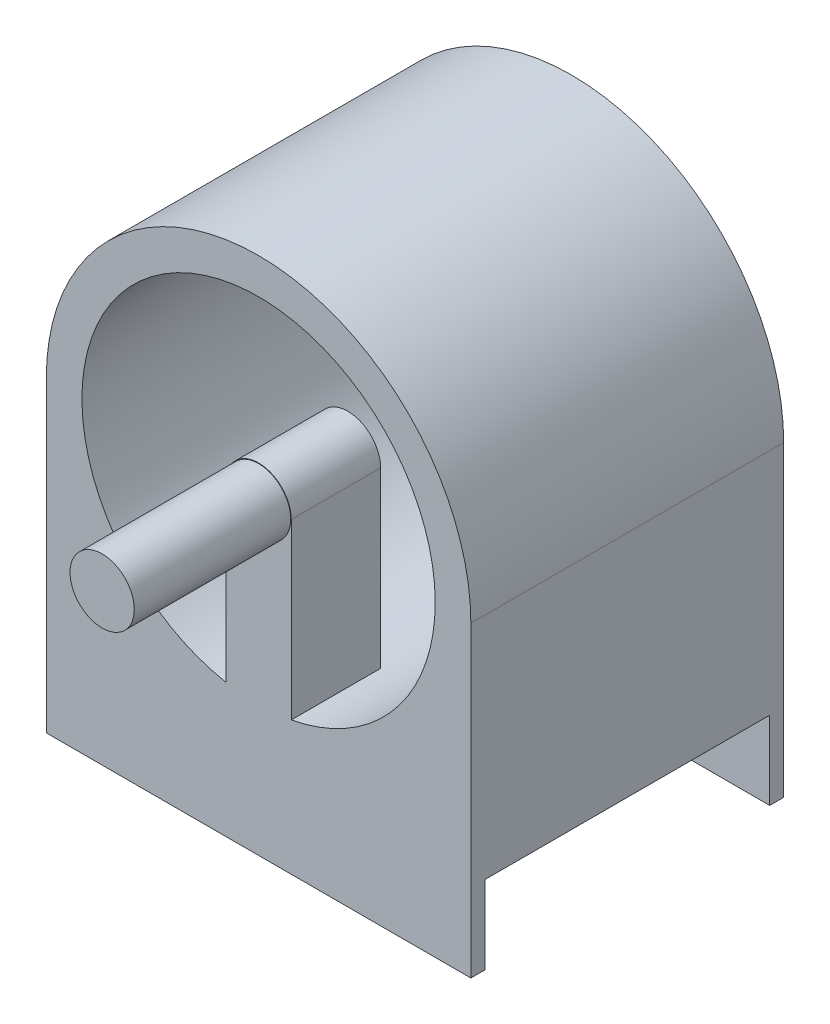
SolidWorks part; units mm, degrees
ref_plane "Front Plane" through (0, 0, 0) normal (0, 0, 1) x (1, 0, 0)
ref_plane "Top Plane" through (0, 0, 0) normal (0, 1, 0) x (1, 0, 0)
ref_plane "Right Plane" through (0, 0, 0) normal (1, 0, 0) x (0, 0, -1)
sketch "Sketch1" plane through (0, 0, 0) normal (1, 0, 0) x (0, 0, -1)
  line L0 (-12.75, 0) -> (-12.75, 7)
  line L1 (-12.75, 7) -> (12.75, 7)
  line L2 (12.75, 7) -> (12.75, 0)
  line L3 (12.75, 0) -> (14, 0)
  line L4 (14, 0) -> (14, 8.5)
  line L5 (14, 8.5) -> (-14, 8.5)
  line L6 (-14, 8.5) -> (-14, 0)
  line L7 (-14, 0) -> (-12.75, 0)
  point P2 (0, 7)
  dimension "D1" = 1.25
  dimension "D2" = 1.25
  dimension "D3" = 1.5
  dimension "D4" = 7
  dimension "D5" = 7
  dimension "D6" = 25.5
extrude "Boss-Extrude1" add sketch "Sketch1" along normal blind 38
sketch "Sketch2" plane through (0, 0, 0) normal (0, 0, 1) x (1, 0, 0)
  line L0 (38, 8.5) -> (0, 8.5) construction
  line L1 (0, 27.5) -> (0, 8.5)
  line L2 (38, 27.5) -> (38, 8.5)
  line L3 (38, 8.5) -> (0, 8.5)
  arc A0 (38, 27.5) -> (0, 27.5) centre (19, 27.5) ccw
  point P7 (19, 8.5)
  dimension "D1" = 38
extrude "Boss-Extrude2" add sketch "Sketch2" along normal mid plane 28
sketch "Sketch3" plane through (0, 0, 14) normal (0, 0, 1) x (1, 0, 0)
  circle A0 centre (19, 27.5) radius 15.81
  dimension "D1" = 31.62
extrude "Cut-Extrude1" cut sketch "Sketch3" against normal through all
sketch "Sketch4" plane through (0, 0, 14) normal (0, 0, 1) x (1, 0, 0)
  line L0 (21.925, 27.5) -> (21.925, 11.9629)
  line L1 (16.075, 27.5) -> (16.075, 11.9629)
  arc A0 (21.925, 27.5) -> (16.075, 27.5) centre (19, 27.5) ccw
  circle A2 centre (19, 27.5) radius 15.81 construction
  arc A3 (16.075, 11.9629) -> (21.925, 11.9629) centre (19, 27.5) ccw
  dimension "D1" = 5.85
extrude "Boss-Extrude3" add sketch "Sketch4" against normal blind 8 contours A0 L1 A3 L0
sketch "Sketch5" plane through (0, 0, 14) normal (0, 0, 1) x (1, 0, 0)
  circle A0 centre (19, 27.5) radius 2.875
  dimension "D1" = 5.75
extrude "Boss-Extrude4" add sketch "Sketch5" along normal blind 14
